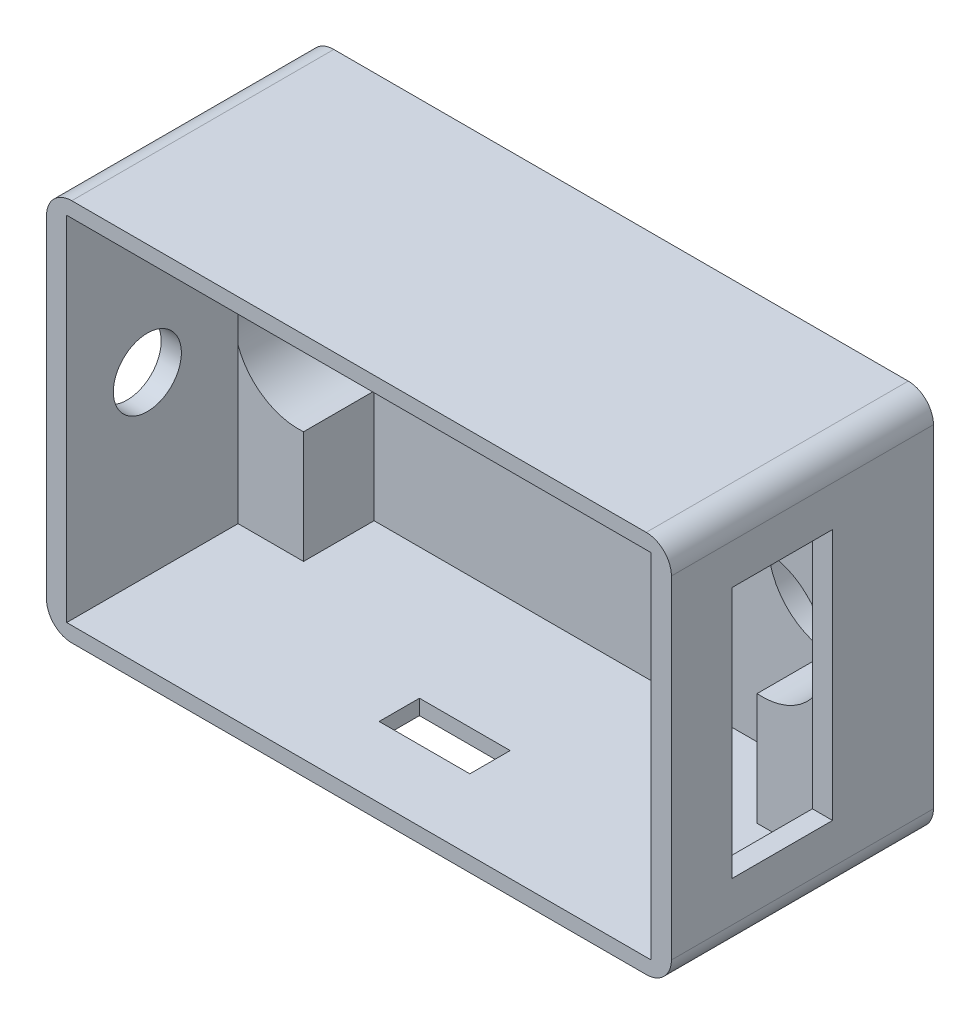
SolidWorks part; units mm, degrees
ref_plane "Front Plane" through (0, 0, 0) normal (0, 0, 1) x (1, 0, 0)
ref_plane "Top Plane" through (0, 0, 0) normal (0, 1, 0) x (1, 0, 0)
ref_plane "Right Plane" through (0, 0, 0) normal (1, 0, 0) x (0, 0, -1)
sketch "Sketch1" plane through (0, 0, 0) normal (0, 0, 1) x (1, 0, 0)
  line L1 (0, 0) -> (62, 0)
  line L2 (0, 0) -> (0, 38)
  line L3 (0, 38) -> (62, 38)
  line L4 (62, 0) -> (62, 38)
  dimension "D1" = 62
  dimension "D2" = 38
extrude "Boss-Extrude1" add sketch "Sketch1" along normal blind 26
sketch "Sketch2" plane through (0, 0, 26) normal (0, 0, 1) x (1, 0, 0)
  line L0 (62, 38) -> (0, 38) construction
  line L1 (2, 36.5) -> (60, 36.5)
  line L2 (2, 36.5) -> (2, 1.5)
  line L3 (2, 1.5) -> (60, 1.5)
  line L4 (60, 36.5) -> (60, 1.5)
  line L6 (0, 38) -> (0, 0) construction
  dimension "D1" = 35
  dimension "D2" = 1.5
  dimension "D3" = 2
  dimension "D4" = 58
extrude "Cut-Extrude1" cut sketch "Sketch2" against normal blind 17
sketch "Sketch4" plane through (0, 0, 9) normal (0, 0, 1) x (1, 0, 0)
  line L1 (8.5, 36.5) -> (53.5, 36.5)
  line L2 (8.5, 36.5) -> (8.5, 1.5)
  line L3 (8.5, 1.5) -> (53.5, 1.5)
  line L4 (53.5, 36.5) -> (53.5, 1.5)
  line L5 (2, 1.5) -> (60, 1.5) construction
  line L6 (2, 36.5) -> (2, 1.5) construction
  dimension "D1" = 35
  dimension "D2" = 45
  dimension "D3" = 0
  dimension "D4" = 6.5
extrude "Cut-Extrude3" cut sketch "Sketch4" against normal blind 7
sketch "Sketch5" plane through (0, 0, 0) normal (0, 0, -1) x (-1, 0, 0)
  line L0 (-62, 0) -> (-62, 38) construction
  line L2 (-62, 38) -> (0, 38) construction
  circle A0 centre (-54, 19) radius 6.375
  circle A1 centre (-8, 19) radius 6.375
  dimension "D1" = 12.75
  dimension "D2" = 12.75
  dimension "D4" = 8
  dimension "D5" = 19
  dimension "D3" = 46
extrude "Cut-Extrude4" cut sketch "Sketch5" against normal blind 9
sketch "Sketch6" plane through (62, 0, 0) normal (1, 0, 0) x (0, 0, -1)
  line L0 (-26, 0) -> (-26, 38) construction
  line L1 (-20, 31.5) -> (-10.0107, 31.5)
  line L2 (-20, 31.5) -> (-20, 6.5)
  line L3 (-20, 6.5) -> (-10.0107, 6.5)
  line L4 (-10.0107, 31.5) -> (-10.0107, 6.5)
  line L5 (-26, 38) -> (0, 38) construction
  dimension "D1" = 6
  dimension "D2" = 6.5
  dimension "D3" = 25
extrude "Cut-Extrude5" cut sketch "Sketch6" against normal blind 17
sketch "Sketch7" plane through (0, 0, 0) normal (-1, 0, 0) x (0, 0, 1)
  line L0 (26, 38) -> (26, 0) construction
  line L1 (26, 38) -> (0, 38) construction
  circle A0 centre (18, 19) radius 3.375
  dimension "D1" = 6.75
  dimension "D3" = 19
  dimension "D2" = 8
extrude "Cut-Extrude6" cut sketch "Sketch7" against normal blind 7
sketch "Sketch8" plane through (0, 0, 0) normal (0, -1, 0) x (1, 0, 0)
  line L0 (62, 26) -> (62, 0) construction
  line L1 (26, 19) -> (35, 19)
  line L2 (26, 19) -> (26, 15)
  line L3 (26, 15) -> (35, 15)
  line L4 (35, 19) -> (35, 15)
  line L7 (0, 0) -> (62, 0) construction
  dimension "D1" = 9
  dimension "D2" = 4
  dimension "D3" = 27
  dimension "D4" = 15
extrude "Cut-Extrude7" cut sketch "Sketch8" against normal blind 7
fillet "Fillet1" radius 2.5 4 edges at (62, 38, 13) (62, 0, 13) (0, 0, 13) (0, 38, 13)
